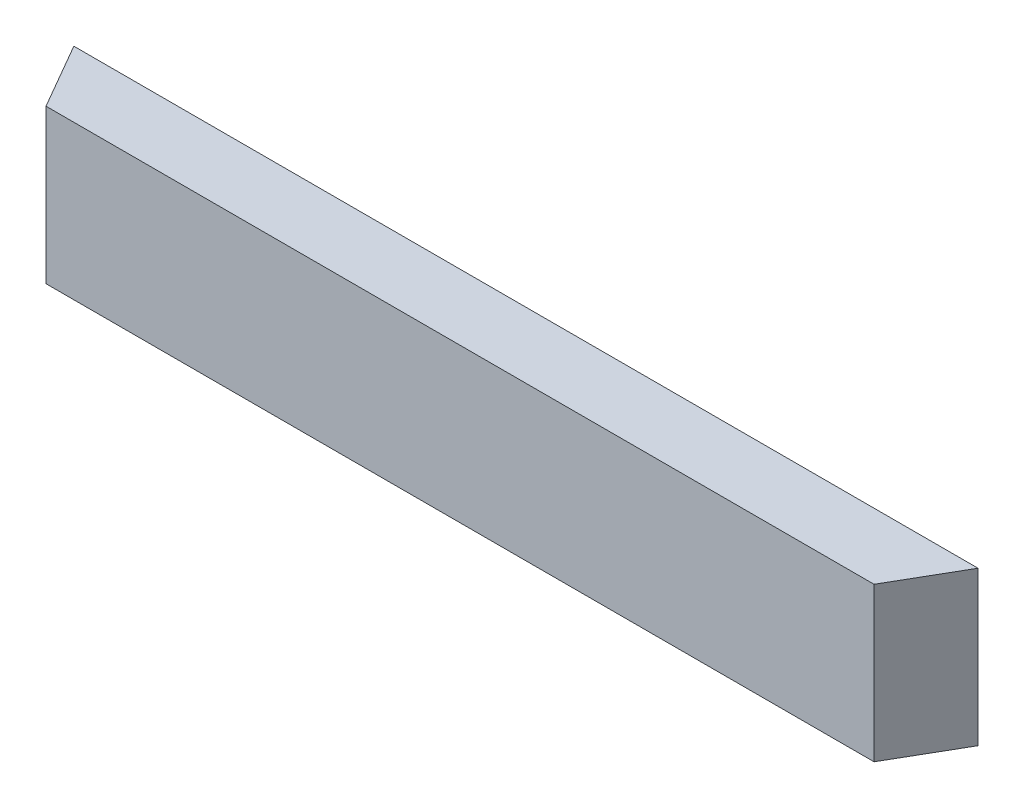
SolidWorks part; units mm, degrees
ref_plane "Front Plane" through (0, 0, 0) normal (0, 0, 1) x (1, 0, 0)
ref_plane "Top Plane" through (0, 0, 0) normal (0, 1, 0) x (1, 0, 0)
ref_plane "Right Plane" through (0, 0, 0) normal (1, 0, 0) x (0, 0, -1)
sketch "Sketch1" plane through (0, 0, 0) normal (0, 1, 0) x (1, 0, 0)
  line L0 (0, 0) -> (478.79, 0)
  line L1 (478.79, 0) -> (500.787, 38.1)
  line L2 (500.787, 38.1) -> (-21.997, 38.1)
  line L3 (-21.997, 38.1) -> (0, 0)
  point P0 (0, 0)
  point P3 (-45.3856, -4.2932)
  point P7 (0, 0)
  dimension "D1" = 60
  dimension "D2" = 60
  dimension "D3" = 38.1
  dimension "D4" = 478.79
extrude "Boss-Extrude1" add sketch "Sketch1" along normal blind 88.9
